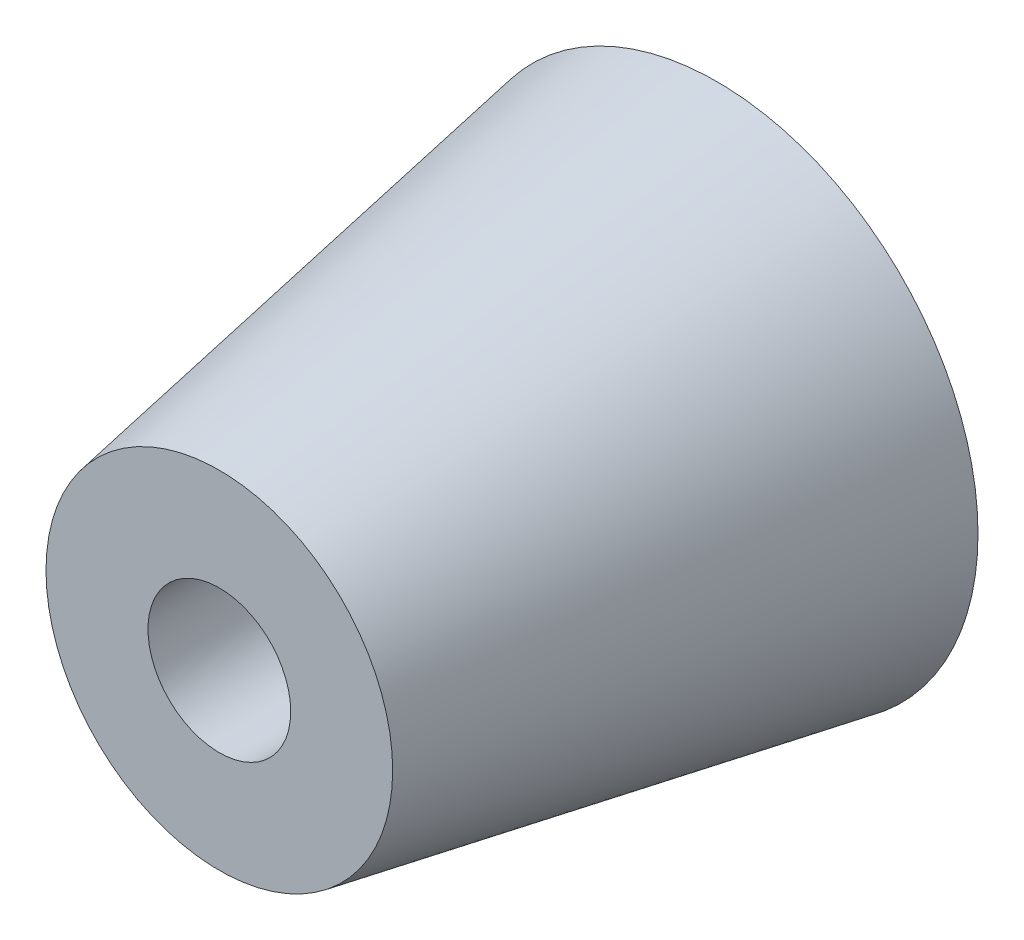
SolidWorks part; units mm, degrees
material "ABS"
ref_plane "Front Plane" through (0, 0, 0) normal (0, 0, 1) x (1, 0, 0)
ref_plane "Top Plane" through (0, 0, 0) normal (0, 1, 0) x (1, 0, 0)
ref_plane "Right Plane" through (0, 0, 0) normal (1, 0, 0) x (0, 0, -1)
sketch "Sketch1" plane through (0, 0, 0) normal (1, 0, 0) x (0, 0, -1)
  line L0 (-51.4955, 0) -> (51.4955, 0) construction
  line L1 (-33.7154, 3.5) -> (-28.7154, 3.5)
  line L2 (-33.7154, 8.5) -> (-9.3154, 12.8024)
  line L4 (-9.3154, 12.8024) -> (-9.3154, 7.2581)
  line L5 (-33.7154, 8.5) -> (-33.7154, 3.5)
  line L11 (-28.7154, 3.5) -> (-9.3154, 7.2581)
  dimension "D2" = 5
  dimension "D5" = 5
  dimension "D7" = 3.5
revolve "Revolve1" add sketch "Sketch1" angle 360 about L0
